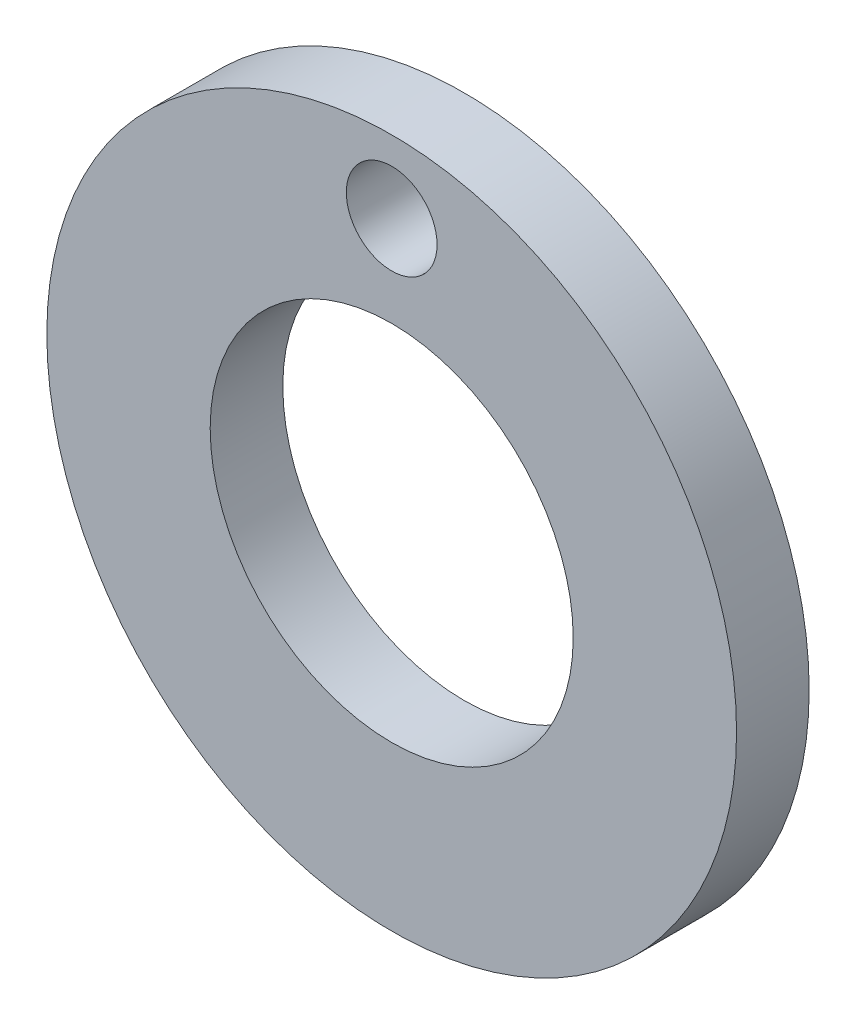
SolidWorks part; units mm, degrees
ref_plane "Alzado" through (0, 0, 0) normal (0, 0, 1) x (1, 0, 0)
ref_plane "Planta" through (0, 0, 0) normal (0, 1, 0) x (1, 0, 0)
ref_plane "Vista lateral" through (0, 0, 0) normal (1, 0, 0) x (0, 0, -1)
sketch "Croquis1" plane through (0, 0, 0) normal (0, 0, 1) x (1, 0, 0)
  circle A0 centre (0, 0) radius 9.5
  circle A1 centre (0, 0) radius 5
  circle A3 centre (0, 0) radius 7.5
  circle A4 centre (0, 7.5) radius 1.25
  dimension "D1" = 10
  dimension "D2" = 19
  dimension "D3" = 2.5
  dimension "D4" = 15
extrude "Saliente-Extruir1" add sketch "Croquis1" along normal blind 2
